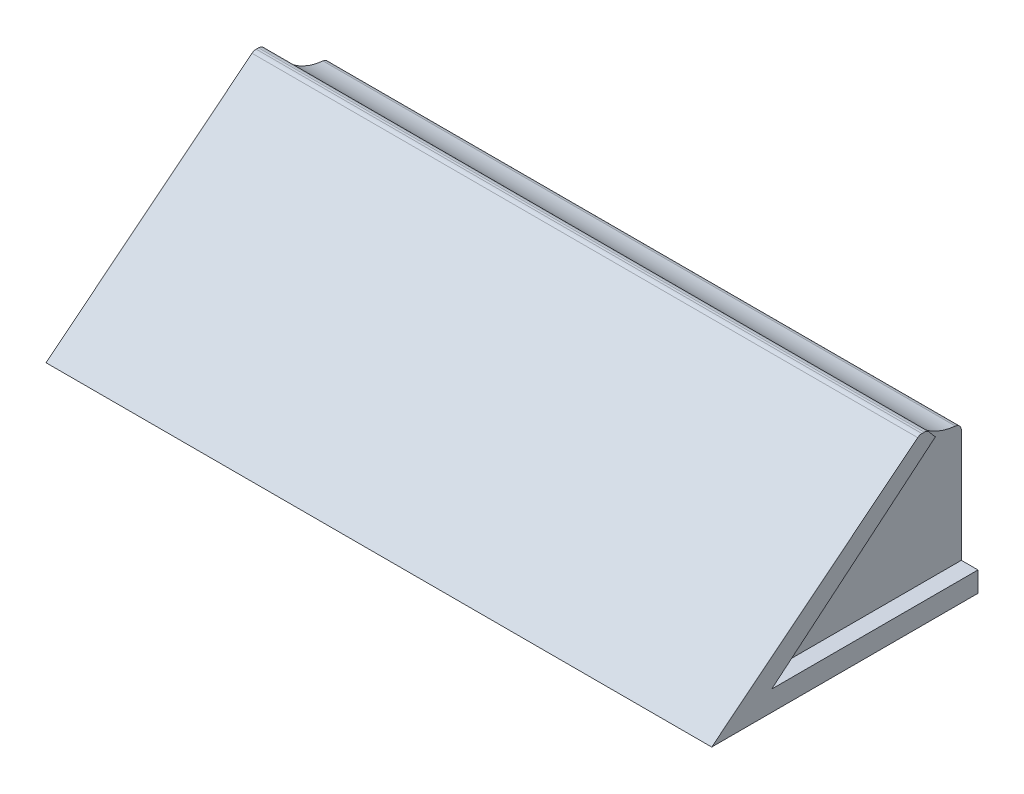
SolidWorks part; units mm, degrees
ref_plane "Front Plane" through (0, 0, 0) normal (0, 0, 1) x (1, 0, 0)
ref_plane "Top Plane" through (0, 0, 0) normal (0, 1, 0) x (1, 0, 0)
ref_plane "Right Plane" through (0, 0, 0) normal (1, 0, 0) x (0, 0, -1)
sketch "Sketch1" plane through (0, 0, 0) normal (0, 0, 1) x (1, 0, 0)
  line L1 (0, 0) -> (-100, 0)
  line L2 (0, 0) -> (0, 25)
  line L3 (0, 25) -> (-100, 25)
  line L4 (-100, 0) -> (-100, 25)
  dimension "D1" = 25
  dimension "D2" = 100
extrude "Boss-Extrude1" add sketch "Sketch1" along normal blind 40
sketch "Sketch2" plane through (0, 0, 0) normal (1, 0, 0) x (0, 0, -1)
  line L0 (-40, 0) -> (-8.7768, 25)
  line L1 (-40, 25) -> (0, 25) construction
extrude "Cut-Extrude2" cut sketch "Sketch2" against normal through all and the other way through all
sketch "Sketch3" plane through (0, 0, 0) normal (1, 0, 0) x (0, 0, -1)
  line L0 (-8.7768, 25) -> (0, 25) construction
  line L1 (0, 0) -> (0, 25) construction
  arc A0 (-7.55, 25) -> (0, 20.9105) centre (-0.0017, 29.9214) ccw
extrude "Cut-Extrude3" cut sketch "Sketch3" against normal through all and the other way through all
fillet "Fillet1" radius 1 1 edges at (-50, 25, 8.7768)
fillet "Fillet2" radius 1 1 edges at (-50, 25, 7.55)
fillet "Fillet3" radius 1 1 edges at (-50, 20.9105, 0)
sketch "Sketch4" plane through (0, 0, 0) normal (1, 0, 0) x (0, 0, -1)
  line L0 (0, 3.0442) -> (-30.9905, 3.0442)
  line L1 (0, 0) -> (0, 19.9604) construction
  line L2 (-30.9905, 3.0442) -> (-6.3923, 23.5687)
  arc A0 (-7.2673, 24.5915) -> (-0.9003, 20.9554) centre (-0.0017, 29.9214) ccw construction
extrude "Cut-Extrude5" cut sketch "Sketch4" against normal blind 2.5 and the other way through all flip side to cut
sketch "Sketch5" plane through (-100, 0, 0) normal (-1, 0, 0) x (0, 0, 1)
  line L0 (0, 3.0442) -> (30.8251, 3.0442)
  line L1 (30.8251, 3.0442) -> (6.3795, 23.5558)
  arc A0 (0.9003, 20.9554) -> (7.2673, 24.5915) centre (0.0017, 29.9214) ccw construction
extrude "Cut-Extrude6" cut sketch "Sketch5" against normal blind 2.5 and the other way through all
